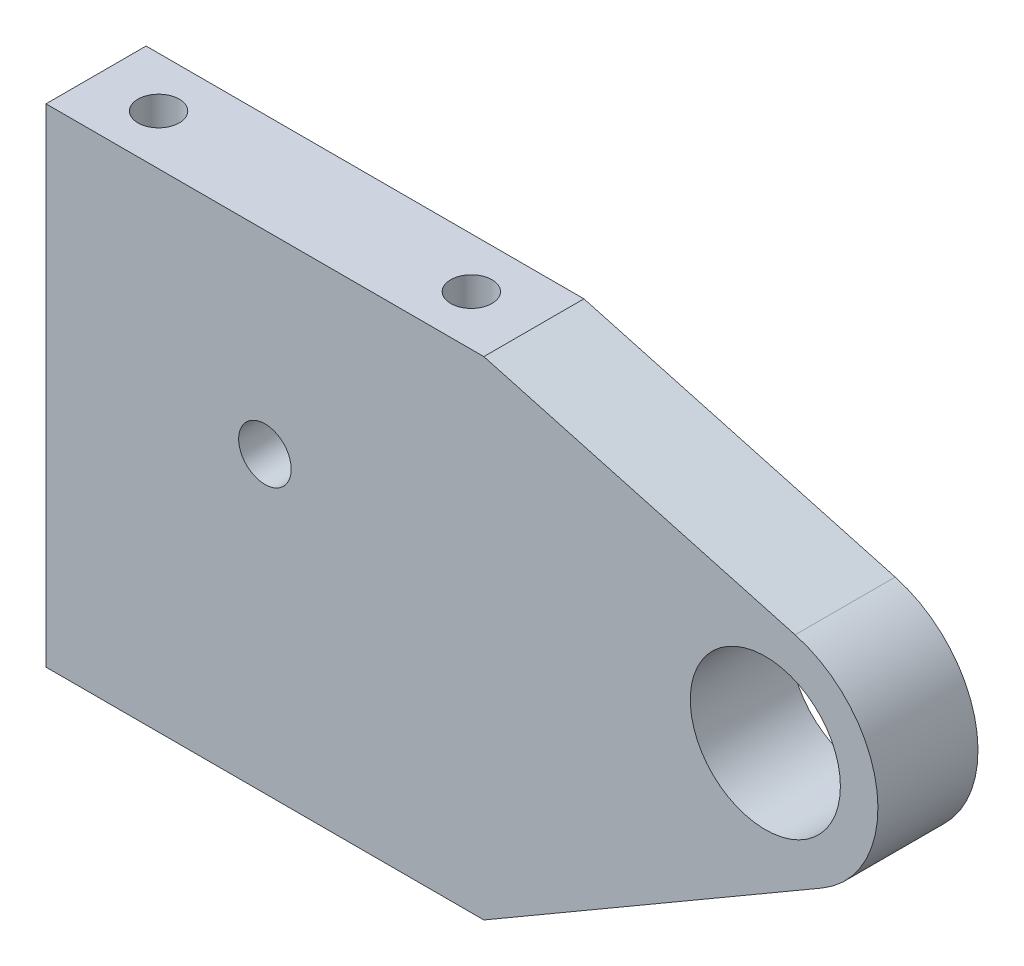
SolidWorks part; units mm, degrees
other "细节项目1"
material "6061-T6 (SS)"
ref_plane "前视基准面" through (0, 0, 0) normal (0, 0, 1) x (1, 0, 0)
ref_plane "上视基准面" through (0, 0, 0) normal (0, 1, 0) x (1, 0, 0)
ref_plane "右视基准面" through (0, 0, 0) normal (1, 0, 0) x (0, 0, -1)
sketch "草图1" plane through (0, 0, 0) normal (0, 0, 1) x (1, 0, 0)
  line L0 (17.5, 39) -> (17.5, 23.5) construction
  line L1 (0, 0) -> (35, 0)
  line L2 (0, 0) -> (0, 39)
  line L3 (0, 39) -> (35, 39)
  line L4 (35, 0) -> (35, 39)
  circle A0 centre (17.5, 23.5) radius 2.1
  dimension "D3" = 4.2
  dimension "D1" = 39
  dimension "D2" = 35
  dimension "D4" = 15.5
extrude "凸台-拉伸1" add sketch "草图1" along normal blind 8
cosmetic thread "装饰螺纹线5" parameters "D2"=5
sketch "草图2" plane through (0, 39, 0) normal (0, 1, 0) x (1, 0, 0)
  line L0 (0, -4) -> (5, -4) construction
  line L1 (0, -8) -> (0, 0) construction
  line L2 (5, -4) -> (30, -4) construction
  line L3 (30, -4) -> (35, -4) construction
  line L4 (35, -8) -> (35, 0) construction
  circle A0 centre (5, -4) radius 1.6
  circle A1 centre (30, -4) radius 1.6
  dimension "D2" = 3.2
  dimension "D1" = 25
extrude "切除-拉伸1" cut sketch "草图2" against normal through all
sketch "草图5" plane through (0, 0, 8) normal (0, 0, 1) x (1, 0, 0)
  line L0 (35, 39) -> (59.8794, 32.1798)
  line L1 (62.0253, 15.7204) -> (35, 0)
  line L2 (35, 0) -> (35, 39)
  line L3 (17.5, 23.5) -> (57.5, 23.5) construction
  circle A0 centre (57.5, 23.5) radius 6
  arc A1 (59.8794, 32.1798) -> (62.0253, 15.7204) centre (57.5, 23.5) cw
  dimension "D1" = 12
  dimension "D2" = 9
  dimension "D3" = 40
extrude "凸台-拉伸3" add sketch "草图5" against normal up to surface (8 mm away) up to face at (17.5, 19.5, 0)
hole_wizard "M4x0.7 螺纹孔1" positions "草图8" profile "草图9" tap size "M4x0.7" standard "ANSI Metric" end condition through all
sketch "草图8" plane through (0, 39, 0) normal (0, 1, 0) x (1, 0, 0)
  point P0 (5, -4)
  point P3 (30, -4)
sketch "草图9" plane through (5, 39, 4) normal (1, 0, 0) x (0, 0, 1)
  line L0 (0, 0) -> (0, 39)
  line L1 (0, 39) -> (1.65, 39)
  line L2 (1.65, 39) -> (1.65, 0)
  line L5 (1.65, 0) -> (0, 0)
  line L11 (0, -6.35) -> (0, 107.95) construction
  dimension "通孔螺纹孔钻头直径" = 3.3
  dimension "通孔螺纹孔钻头深度" = 39
cosmetic thread "孔螺蚊线1" parameters "D2"=4
cosmetic thread "孔螺蚊线2" parameters "D2"=4
